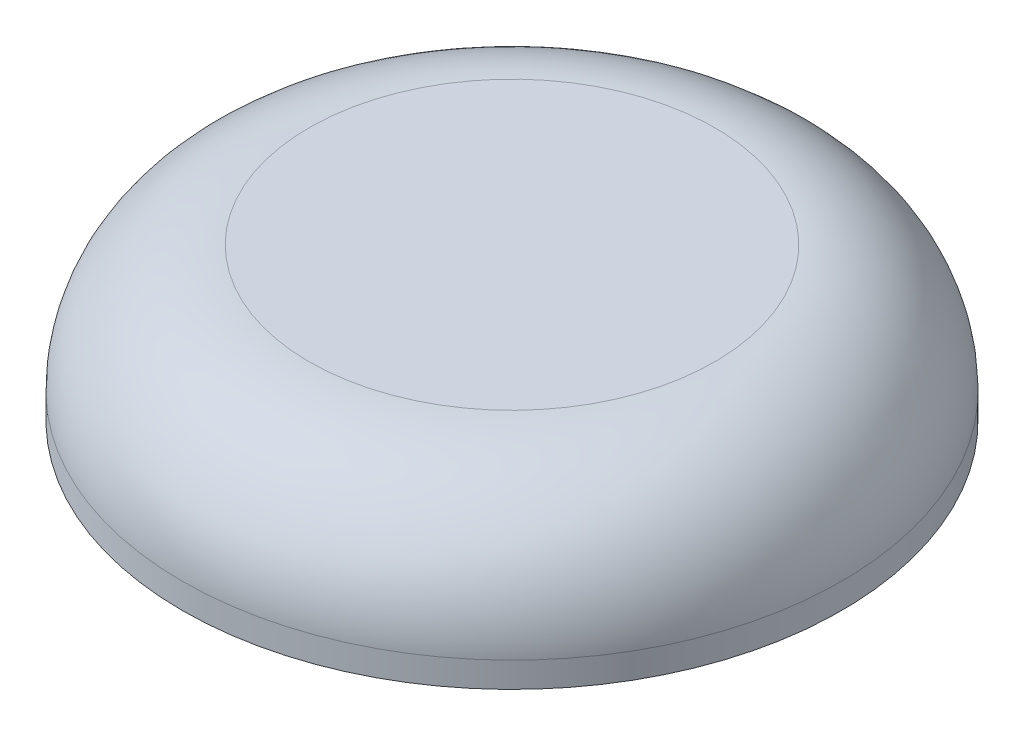
SolidWorks part; units mm, degrees
ref_plane "Front Plane" through (0, 0, 0) normal (0, 0, 1) x (1, 0, 0)
ref_plane "Top Plane" through (0, 0, 0) normal (0, 1, 0) x (1, 0, 0)
ref_plane "Right Plane" through (0, 0, 0) normal (1, 0, 0) x (0, 0, -1)
sketch "Sketch1" plane through (0, 0, 0) normal (0, 1, 0) x (1, 0, 0)
  circle A0 centre (0, 0) radius 6.5
  dimension "D1" = 13
extrude "Boss-Extrude1" add sketch "Sketch1" along normal blind 3
fillet "Fillet3" radius 2.5 1 edges at (0, 3, 6.5)
